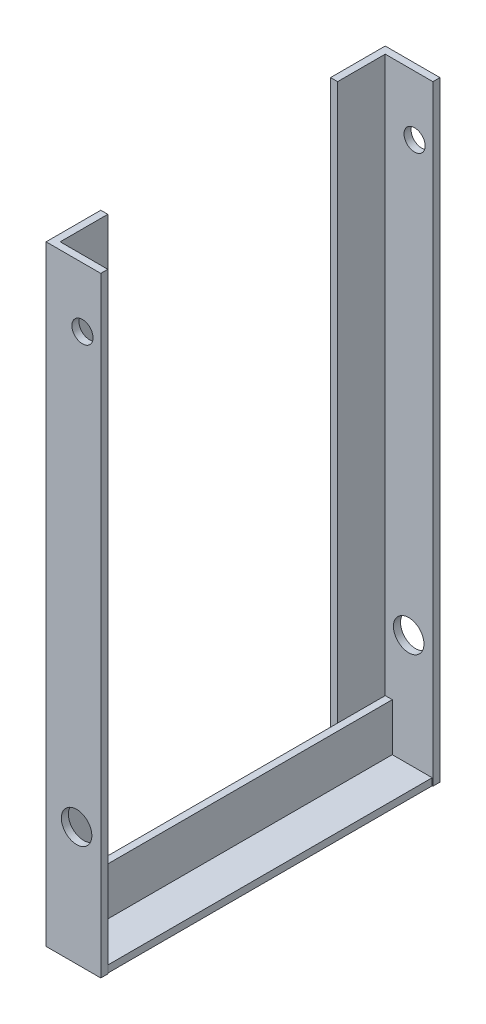
SolidWorks part; units mm, degrees
ref_plane "Front Plane" through (0, 0, 0) normal (0, 0, 1) x (1, 0, 0)
ref_plane "Top Plane" through (0, 0, 0) normal (0, 1, 0) x (1, 0, 0)
ref_plane "Right Plane" through (0, 0, 0) normal (1, 0, 0) x (0, 0, -1)
sketch "Sketch1" plane through (0, 0, 0) normal (1, 0, 0) x (0, 0, -1)
  line L1 (-1.5, 130) -> (1.5, 130)
  line L2 (-1.5, 130) -> (-1.5, -130)
  line L3 (-1.5, -130) -> (1.5, -130)
  line L4 (1.5, 130) -> (1.5, -130)
  line L5 (-1.5, 130) -> (1.5, -130) construction
  line L6 (-1.5, -130) -> (1.5, 130) construction
  point P0 (0, 0)
  dimension "D1" = 3
  dimension "D2" = 260
extrude "Boss-Extrude1" add sketch "Sketch1" along normal blind 3
sketch "Sketch2" plane through (3, 0, 0) normal (1, 0, 0) x (0, 0, -1)
  line L0 (-1.5, -130) -> (1.5, -130) construction
  line L1 (-1.5, 130) -> (1.5, 130)
  line L2 (-1.5, 130) -> (-1.5, -130)
  line L3 (-1.5, -130) -> (1.5, -130)
  line L4 (1.5, 130) -> (1.5, -130)
  dimension "D1" = 3
extrude "Boss-Extrude2" add sketch "Sketch2" along normal blind 20.3
sketch "Sketch3" plane through (0, 0, 1.5) normal (0, 0, 1) x (1, 0, 0)
  line L2 (15.5, 104.6) -> (0, 104.6) construction
  circle A0 centre (15.5, 104.6) radius 4.5
  dimension "D2" = 9
  dimension "D1" = 15.5
extrude "Cut-Extrude1" cut sketch "Sketch3" against normal blind 20.3 and the other way blind 22.3
ref_plane "Plane1" through (0, 0, 70.75) normal (0, 0, 1) x (1, 0, 0)
ref_plane "Plane2" through (0, 0, 140) normal (0, 0, 1) x (1, 0, 0)
sketch "Sketch5" plane through (0, 0, 140) normal (0, 0, 1) x (1, 0, 0)
  line L0 (11.65, 130) -> (11.65, -130) construction
  line L1 (23.3, 130) -> (0, 130) construction
  line L2 (23.3, -130) -> (0, -130) construction
  line L3 (11.65, 0) -> (23.4759, 0) construction
  line L4 (0, 130) -> (0, -130) construction
  line L5 (0, -130) -> (23.3, -130)
  line L6 (0, -130) -> (0, 130)
  line L7 (0, 130) -> (23.3, 130)
  line L8 (23.3, -130) -> (23.3, 130)
  line L9 (0, -130) -> (23.3, 130) construction
  line L10 (0, 130) -> (23.3, -130) construction
extrude "Boss-Extrude3" add sketch "Sketch5" along normal blind 3 separate body
sketch "Sketch6" plane through (0, 0, 143) normal (0, 0, 1) x (1, 0, 0)
  line L0 (0, -130) -> (23.3, -130) construction
  line L1 (0, 130) -> (3, 130)
  line L2 (0, 130) -> (0, -130)
  line L3 (0, -130) -> (3, -130)
  line L4 (3, 130) -> (3, -130)
  dimension "D1" = 3
sketch "Sketch7" plane through (0, 0, 140) normal (0, 0, -1) x (-1, 0, 0)
  line L0 (-15.5, 104.6) -> (0, 104.6) construction
  line L1 (0, 130) -> (0, -130) construction
  circle A0 centre (-15.5, 104.6) radius 4.5
  dimension "D1" = 9
extrude "Boss-Extrude4" add sketch "Sketch6" against normal blind 23.3
sketch "Sketch8" plane through (0, 0, 1.5) normal (0, 0, 1) x (1, 0, 0)
  line L0 (23.3, -130) -> (0, -130) construction
  line L1 (0, 130) -> (3, 130)
  line L2 (0, 130) -> (0, -130)
  line L3 (0, -130) -> (3, -130)
  line L4 (3, 130) -> (3, -130)
  dimension "D1" = 3
extrude "Boss-Extrude5" add sketch "Sketch8" along normal blind 20.3
sketch "Sketch10" plane through (0, 0, -1.5) normal (0, 0, -1) x (-1, 0, 0)
  line L0 (-13, -79.4) -> (0, -79.4) construction
  line L1 (0, -130) -> (0, 130) construction
  circle A0 centre (-13, -79.4) radius 6.5
  dimension "D2" = 13
  dimension "D1" = 13
sketch "Sketch11" plane through (3, 0, 0) normal (1, 0, 0) x (0, 0, -1)
  line L0 (1.5, -130) -> (1.5, 130) construction
  line L1 (-143, -130) -> (1.5, -130)
  line L2 (-143, -130) -> (-143, -106.7)
  line L3 (-143, -106.7) -> (1.5, -106.7)
  line L4 (1.5, -130) -> (1.5, -106.7)
  dimension "D1" = 23.3
extrude "Boss-Extrude6" add sketch "Sketch11" along normal blind 3
sketch "Sketch12" plane through (6, 0, 0) normal (1, 0, 0) x (0, 0, -1)
  line L0 (-140, 12.815) -> (-140, -12.815) construction
  line L1 (-1.5, -130) -> (-140, -130)
  line L2 (-1.5, -130) -> (-1.5, -127)
  line L3 (-1.5, -127) -> (-140, -127)
  line L4 (-140, -130) -> (-140, -127)
  dimension "D1" = 3
extrude "Boss-Extrude7" add sketch "Sketch12" along normal blind 17
extrude "Cut-Extrude3" cut sketch "Sketch10" against normal blind 156
extrude "Cut-Extrude4" cut sketch "Sketch7" against normal blind 10
